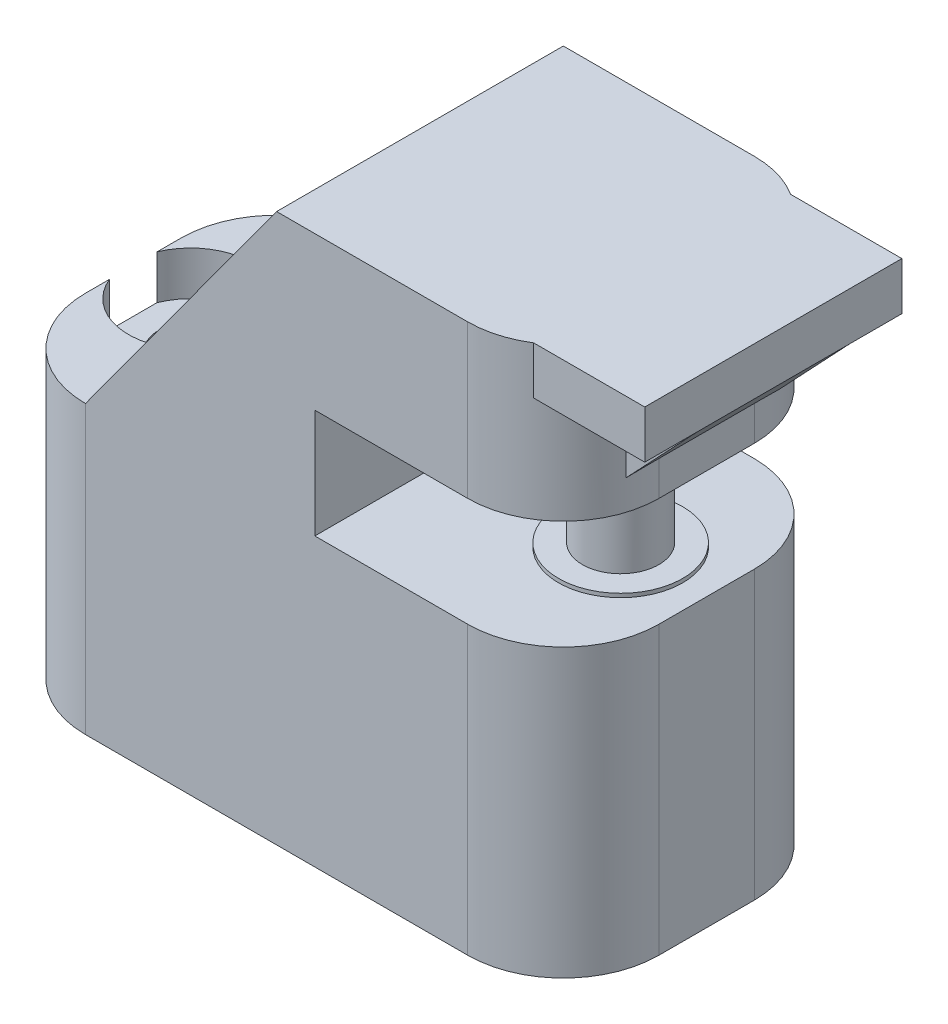
SolidWorks part; units mm, degrees
ref_plane "Front Plane" through (0, 0, 0) normal (0, 0, 1) x (1, 0, 0)
ref_plane "Top Plane" through (0, 0, 0) normal (0, 1, 0) x (1, 0, 0)
ref_plane "Right Plane" through (0, 0, 0) normal (1, 0, 0) x (0, 0, -1)
sketch "Sketch1" plane through (0, 0, 0) normal (0, 0, 1) x (1, 0, 0)
  line L0 (0, 0) -> (0, 15)
  line L1 (0, 15) -> (5, 15)
  line L2 (5, 15) -> (15, 28.7)
  line L3 (15, 28.7) -> (30, 28.7)
  line L4 (30, 28.7) -> (30, 20.7)
  line L5 (30, 20.7) -> (17, 20.7)
  line L6 (17, 20.7) -> (17, 15)
  line L7 (17, 15) -> (30, 15)
  line L8 (30, 15) -> (30, 0)
  line L9 (30, 0) -> (0, 0)
  dimension "D1" = 13
  dimension "D2" = 5.7
  dimension "D3" = 30
  dimension "D5" = 8
  dimension "D6" = 15
  dimension "D7" = 5
  dimension "D8" = 15
extrude "Boss-Extrude1" add sketch "Sketch1" along normal blind 15
ref_plane "Plane1" through (0, 17.85, 0) normal (0, 1, 0) x (1, 0, 0)
sketch "Sketch3" plane through (0, 15, 0) normal (0, 1, 0) x (1, 0, 0)
  line L0 (30, -15) -> (30, 0) construction
  line L1 (17, -15) -> (17, 0) construction
  circle A0 centre (25.5, -7.5) radius 2
  circle A1 centre (25.5, -7.5) radius 6.5 construction
  point P4 (30, -7.5)
  dimension "D1" = 4
  dimension "D2" = 8.5
  dimension "D3" = 13
extrude "Boss-Extrude2" add sketch "Sketch3" along normal up to next
sketch "Sketch4" plane through (0, 15, 0) normal (0, 1, 0) x (1, 0, 0)
  circle A0 centre (25.5, -7.5) radius 3.25
  dimension "D1" = 6.5
extrude "Boss-Extrude3" add sketch "Sketch4" along normal blind 0.2
mirror "Mirror1" about plane through (0, 17.85, 0) normal (0, 1, 0) of "Boss-Extrude3"
fillet "Fillet1" radius 5 6 edges at (30, 24.7, 0) (30, 24.7, 15) (30, 7.5, 0) (30, 7.5, 15) (0, 7.5, 0) (0, 7.5, 15)
sketch "Sketch5" plane through (0, 28.7, 0) normal (0, 1, 0) x (1, 0, 0)
  line L0 (0, -10) -> (0, -5) construction
  point P0 (3, -7.5)
  point P1 (10, -7.5)
  point P4 (0, -7.5)
  dimension "D1" = 7
  dimension "D2" = 3
hole_wizard "CBORE for M3 SHCS1" positions "Sketch5" profile "Sketch6" counterbore size "M3" standard "ANSI Metric" end condition through all
sketch "Sketch6" plane through (3, 28.7, 7.5) normal (1, 0, 0) x (0, 0, 1)
  line L0 (0, 0) -> (0, 28.7)
  line L1 (0, 28.7) -> (1.7, 28.7)
  line L3 (1.7, 28.7) -> (1.7, 16)
  line L4 (3.25, 16) -> (1.7, 16)
  line L5 (3.25, 16) -> (3.25, 0.025)
  line L6 (3.25, 0.025) -> (3.275, 0)
  line L7 (3.275, 0) -> (0, 0)
  line L8 (-3.25, 0.025) -> (-3.275, 0) construction
  line L11 (0, -6.35) -> (0, 107.95) construction
  dimension "Thru Hole Dia." = 3.4
  dimension "Thru Hole Depth" = 28.7
  dimension "C'Bore Dia." = 6.5
  dimension "C'Bore Depth" = 16
  dimension "Near C'Sink Dia." = 6.55
  dimension "Near C'Sink Angle" = 90
sketch "Sketch7" plane through (0, 28.7, 0) normal (0, 1, 0) x (1, 0, 0)
  line L1 (33.4869, -0.7742) -> (27.6726, -0.7742)
  line L2 (33.4869, -0.7742) -> (33.4869, -14.2258)
  line L3 (33.4869, -14.2258) -> (27.6726, -14.2258)
  line L4 (27.6726, -0.7742) -> (27.6726, -14.2258)
  arc A1 (25, -15) -> (30, -10) centre (25, -10) ccw construction
  arc A2 (30, -5) -> (25, 0) centre (25, -5) ccw construction
  point P4 (0, 0)
extrude "Boss-Extrude4" add sketch "Sketch7" against normal blind 2.5
ref_plane "Plane2" through (0, 0, 7.5) normal (0, 0, 1) x (1, 0, 0)
sketch "Sketch9" plane through (0, 0, 7.5) normal (0, 0, 1) x (1, 0, 0)
  line L0 (33.4869, 26.2) -> (30, 22.5075)
  line L1 (30, 26.2) -> (30, 20.7) construction
rib "Rib1" sketch "Sketch9" sketch "Sketch9" thickness 8 extrusion direction parallel to sketch draft on no parameters "D1"=8
